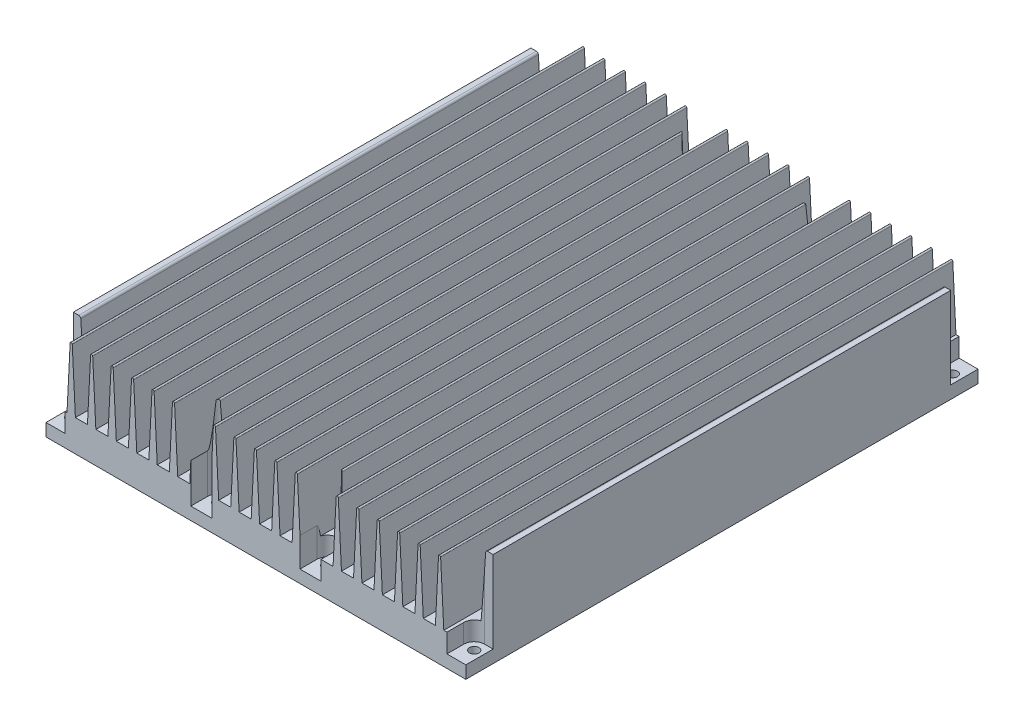
SolidWorks part; units mm, degrees
ref_plane "Спереди" through (0, 0, 0) normal (0, 0, 1) x (1, 0, 0)
ref_plane "Сверху" through (0, 0, 0) normal (0, 1, 0) x (1, 0, 0)
ref_plane "Справа" through (0, 0, 0) normal (1, 0, 0) x (0, 0, -1)
sketch "Эскиз1" plane through (0, 0, 0) normal (0, 0, 1) x (1, 0, 0)
  line L0 (0, 45) -> (2.5644, 45)
  line L1 (0, 0) -> (200, 0)
  line L2 (3.5622, 44.0665) -> (5.5, 15)
  line L3 (0, 45) -> (0, 0)
  line L4 (200, 45) -> (200, 0)
  line L5 (100, 63.7127) -> (100, -22.2582) construction
  line L8 (200, 45) -> (197.4356, 45)
  line L9 (196.4378, 44.0665) -> (194.5, 15)
  line L10 (5.5, 15) -> (194.5, 15)
  arc A0 (2.5644, 45) -> (3.5622, 44.0665) centre (2.5644, 44) cw
  arc A2 (197.4356, 45) -> (196.4378, 44.0665) centre (197.4356, 44) ccw
  point P18 (196.5, 45)
  dimension "D9" = 1
  dimension "D1" = 200
  dimension "D2" = 15
  dimension "D3" = 45
  dimension "D4" = 5.5
  dimension "D7" = 3.5
extrude "Вытянуть1" add sketch "Эскиз1" along normal blind 244
sketch "Эскиз2" plane through (0, 0, 244) normal (0, 0, 1) x (1, 0, 0)
  line L0 (194.5, 15) -> (5.5, 15) construction
  line L1 (11.5, 44.5) -> (10, 15)
  line L2 (12, 44.5) -> (12, 22.5548) construction
  line L3 (12.5, 44.5) -> (14, 15)
  line L4 (10, 15) -> (14, 15)
  line L6 (0, 45) -> (0, 0) construction
  arc A0 (11.5, 44.5) -> (12.5, 44.5) centre (12, 44.5) cw
  dimension "D1" = 30
  dimension "D3" = 0.5
  dimension "D2" = 4
  dimension "D4" = 12
  dimension "D5" = 1
extrude "Вытянуть3" add sketch "Эскиз2" against normal blind 244
pattern_curve "Кривая1" of "Вытянуть3" along edge at (100, 0, 0) parameters "D1"=19, "D3"=9.75, "D2"=1, "D4"=50
sketch "Эскиз3" plane through (0, 0, 0) normal (0, -1, 0) x (1, 0, 0)
  line L0 (11.9208, 236) -> (163.4793, 236) construction
  line L9 (4, 8) -> (74, 8) construction
  line L10 (-13.0453, 122) -> (213.0453, 122) construction
  line L11 (0, 244) -> (200, 244) construction
  line L12 (0, 0) -> (200, 0) construction
  line L13 (100, 122) -> (100, 199.2779) construction
  line L14 (0, 244) -> (0, 0) construction
  line L15 (200, 244) -> (200, 0) construction
  line L16 (4, 8) -> (4, 236) construction
  circle A0 centre (4, 236) radius 2.25
  circle A1 centre (74, 236) radius 2.25
  circle A2 centre (74, 8) radius 2.25
  circle A3 centre (4, 8) radius 2.25
  circle A4 centre (196, 8) radius 2.25
  circle A5 centre (126, 8) radius 2.25
  circle A6 centre (126, 236) radius 2.25
  circle A7 centre (196, 236) radius 2.25
  dimension "D2" = 70
  dimension "D4" = 4.5
  dimension "D1" = 228
  dimension "D3" = 70
  dimension "D5" = 4
extrude "Вырез-Вытянуть1" cut sketch "Эскиз3" against normal blind 50
sketch "Эскиз5" plane through (1.488, 0, 27.4005) normal (0, -1, 0) x (1, 0, 0)
  line L0 (38.512, 61.5995) -> (38.512, 196.5995) construction
  line L1 (169.5663, 109.0995) -> (118.1918, 109.0995) construction
  line L4 (98.512, 232.3889) -> (98.512, 188.3893) construction
  line L5 (-1.488, 216.5995) -> (198.512, 216.5995) construction
  circle A0 centre (43.512, 22.5995) radius 2.1
  circle A1 centre (72.512, 208.5995) radius 2.25 construction
  circle A2 centre (81.512, 109.0995) radius 1.6
  circle A3 centre (38.512, 196.5995) radius 1.6
  circle A4 centre (38.512, 61.5995) radius 1.6
  circle A5 centre (124.512, 208.5995) radius 2.25 construction
  circle A6 centre (158.512, 61.5995) radius 1.6
  circle A7 centre (115.512, 109.0995) radius 1.6
  circle A8 centre (158.512, 196.5995) radius 1.6
  dimension "D2" = 3.2
  dimension "D4" = 3.2
  dimension "D5" = 4.2
  dimension "D7" = 135
  dimension "D8" = 87.5
  dimension "D9" = 60
  dimension "D1" = 39
  dimension "D10" = 20
  dimension "D6" = 5
  dimension "D3" = 43
extrude "Вырез-Вытянуть2" cut sketch "Эскиз5" against normal blind 10
cosmetic thread "Условное изображение резьбы1" parameters "D2"=5
cosmetic thread "Условное изображение резьбы2" parameters "D2"=4
cosmetic thread "Условное изображение резьбы3" parameters "D2"=4
cosmetic thread "Условное изображение резьбы4" parameters "D2"=4
cosmetic thread "Условное изображение резьбы8"
cosmetic thread "Условное изображение резьбы9"
cosmetic thread "Условное изображение резьбы10"
ref_plane "Плоскость1" through (0, 6, 0) normal (0, -1, 0) x (1, 0, 0)
sketch "Эскиз6" plane through (0, 6, 0) normal (0, -1, 0) x (1, 0, 0)
  line L0 (-60.3162, 122) -> (260.3162, 122) construction
  line L1 (0, 244) -> (200, 244) construction
  line L2 (0, 0) -> (200, 0) construction
  line L3 (100, 122) -> (100, 228.6897) construction
  line L4 (0, 244) -> (0, 0) construction
  line L5 (200, 244) -> (200, 0) construction
  line L6 (9, 236) -> (9, 247.6253)
  line L7 (4, 231) -> (-6.1278, 231)
  line L8 (-6.1278, 231) -> (-6.1278, 247.6253)
  line L9 (-6.1278, 247.6253) -> (9, 247.6253)
  line L10 (69, 236) -> (69, 248.9831)
  line L11 (69, 248.9831) -> (79, 248.9831)
  line L12 (79, 248.9831) -> (79, 236)
  line L13 (121, 248.9831) -> (121, 236)
  line L14 (131, 248.9831) -> (121, 248.9831)
  line L15 (131, 236) -> (131, 248.9831)
  line L16 (206.1278, 247.6253) -> (191, 247.6253)
  line L17 (206.1278, 231) -> (206.1278, 247.6253)
  line L18 (196, 231) -> (206.1278, 231)
  line L19 (191, 236) -> (191, 247.6253)
  line L20 (191, 8) -> (191, -3.6253)
  line L21 (196, 13) -> (206.1278, 13)
  line L22 (206.1278, 13) -> (206.1278, -3.6253)
  line L23 (206.1278, -3.6253) -> (191, -3.6253)
  line L24 (131, 8) -> (131, -4.9831)
  line L25 (131, -4.9831) -> (121, -4.9831)
  line L26 (121, -4.9831) -> (121, 8)
  line L27 (79, -4.9831) -> (79, 8)
  line L28 (69, -4.9831) -> (79, -4.9831)
  line L29 (69, 8) -> (69, -4.9831)
  line L30 (-6.1278, -3.6253) -> (9, -3.6253)
  line L31 (-6.1278, 13) -> (-6.1278, -3.6253)
  line L32 (4, 13) -> (-6.1278, 13)
  line L33 (9, 8) -> (9, -3.6253)
  arc A0 (4, 231) -> (9, 236) centre (4, 236) ccw
  arc A1 (69, 236) -> (79, 236) centre (74, 236) ccw
  arc A2 (131, 236) -> (121, 236) centre (126, 236) cw
  arc A3 (196, 231) -> (191, 236) centre (196, 236) cw
  arc A4 (196, 13) -> (191, 8) centre (196, 8) ccw
  arc A5 (131, 8) -> (121, 8) centre (126, 8) ccw
  arc A6 (69, 8) -> (79, 8) centre (74, 8) cw
  arc A7 (4, 13) -> (9, 8) centre (4, 8) cw
  dimension "D1" = 10
  dimension "D2" = 10
extrude "Вырез-Вытянуть3" cut sketch "Эскиз6" against normal blind 80
